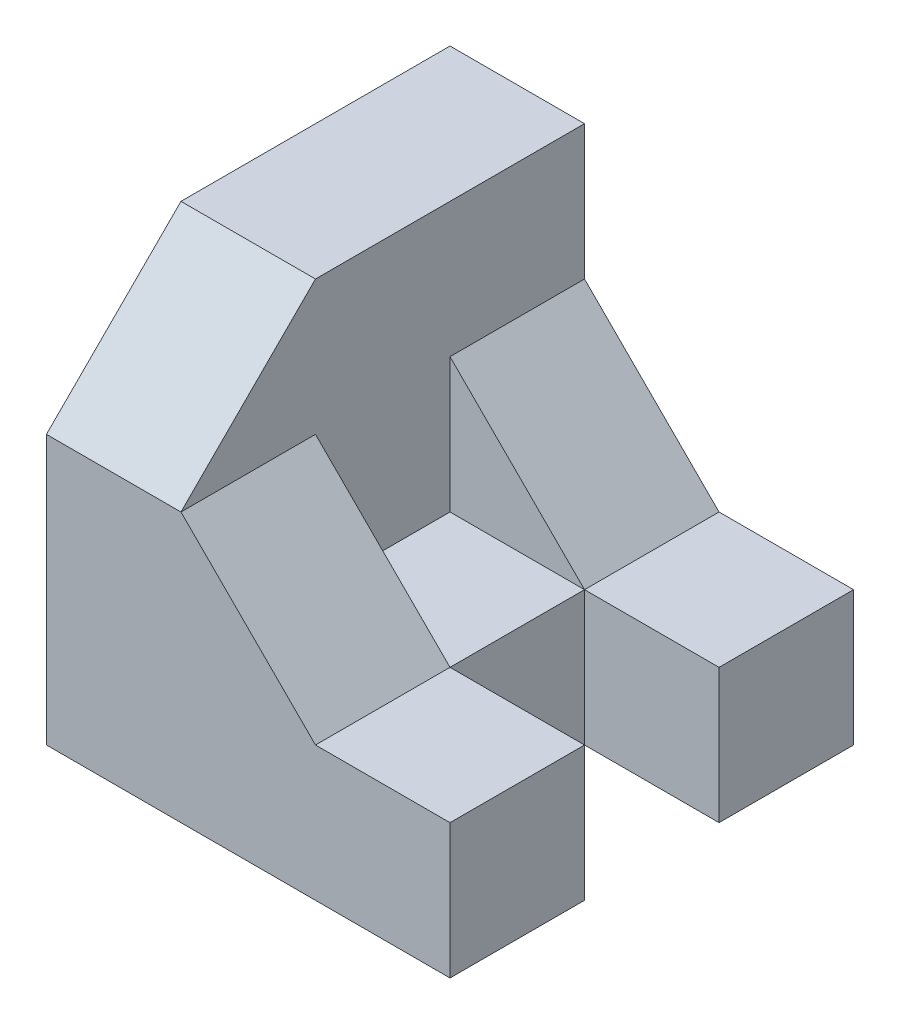
SolidWorks part; units mm, degrees
ref_plane "Alzado" through (0, 0, 0) normal (0, 0, 1) x (1, 0, 0)
ref_plane "Planta" through (0, 0, 0) normal (0, 1, 0) x (1, 0, 0)
ref_plane "Vista lateral" through (0, 0, 0) normal (1, 0, 0) x (0, 0, -1)
sketch "Croquis1" plane through (0, 0, 0) normal (0, 0, 1) x (1, 0, 0)
  line L0 (0, 0) -> (60, 0)
  line L1 (60, 0) -> (60, 60)
  line L2 (60, 60) -> (0, 60)
  line L3 (0, 60) -> (0, 0)
  dimension "D1" = 60
  dimension "D2" = 60
extrude "Saliente-Extruir1" add sketch "Croquis1" against normal blind 60
sketch "Croquis2" plane through (0, 60, 0) normal (0, 1, 0) x (1, 0, 0)
  line L0 (60, 40) -> (20, 40)
  line L1 (60, 60) -> (60, 0) construction
  line L2 (20, 40) -> (20, 20)
  line L3 (20, 20) -> (60, 20)
  line L4 (60, 20) -> (60, 40)
  line L5 (60, 60) -> (0, 60) construction
  line L6 (60, 0) -> (0, 0) construction
  line L7 (0, 60) -> (0, 0) construction
  dimension "D1" = 20
  dimension "D2" = 20
  dimension "D3" = 20
extrude "Cortar-Extruir1" cut sketch "Croquis2" against normal blind 60
sketch "Croquis3" plane through (0, 0, -40) normal (0, 0, 1) x (1, 0, 0)
  line L0 (40, 0) -> (40, 20)
  line L1 (0, 0) -> (60, 0) construction
  line L2 (40, 20) -> (20, 20)
  line L3 (20, 20) -> (20, 0)
  line L4 (20, 0) -> (40, 0)
  line L5 (0, 60) -> (0, 0) construction
  line L6 (60, 0) -> (60, 60) construction
  dimension "D1" = 20
  dimension "D2" = 20
  dimension "D3" = 20
extrude "Saliente-Extruir2" add sketch "Croquis3" along normal blind 20
sketch "Croquis4" plane through (0, 0, -40) normal (0, 0, 1) x (1, 0, 0)
  line L2 (20, 40) -> (40, 20)
  line L3 (40, 20) -> (40, 60)
  line L4 (60, 60) -> (0, 60) construction
  line L5 (40, 60) -> (20, 60)
  line L7 (0, 0) -> (60, 0) construction
  line L8 (60, 0) -> (60, 60) construction
  line L9 (20, 40) -> (20, 60)
  line L10 (40, 20) -> (20, 20) construction
  line L11 (20, 20) -> (20, 40) construction
  dimension "D1" = 20
  dimension "D2" = 20
  dimension "D3" = 20
  dimension "D4" = 40
extrude "Cortar-Extruir2" cut sketch "Croquis4" against normal blind 20
sketch "Croquis5" plane through (0, 0, -20) normal (0, 0, -1) x (-1, 0, 0)
  line L0 (-40, 20) -> (-40, 60)
  line L1 (-40, 60) -> (-20, 60)
  line L2 (-20, 60) -> (-20, 40)
  line L3 (-20, 20) -> (-20, 60) construction
  line L4 (-20, 40) -> (-40, 20)
extrude "Cortar-Extruir3" cut sketch "Croquis5" against normal blind 20
sketch "Croquis6" plane through (20, 0, 0) normal (1, 0, 0) x (0, 0, -1)
  line L0 (0, 40) -> (20, 60)
  line L1 (20, 60) -> (0, 60)
  line L2 (0, 60) -> (0, 40)
extrude "Cortar-Extruir4" cut sketch "Croquis6" against normal blind 20
sketch "Croquis7" plane through (0, 60, 0) normal (0, 1, 0) x (1, 0, 0)
  line L0 (40, 60) -> (40, 40)
  line L1 (40, 40) -> (60, 40)
  line L2 (60, 40) -> (60, 60)
  line L3 (60, 60) -> (40, 60)
extrude "Cortar-Extruir5" cut sketch "Croquis7" against normal blind 40
sketch "Croquis9" plane through (0, 60, 0) normal (0, 1, 0) x (1, 0, 0)
  line L0 (40, 20) -> (40, 0)
  line L1 (40, 0) -> (60, 0)
  line L2 (60, 0) -> (60, 20)
  line L3 (60, 20) -> (40, 20)
extrude "Cortar-Extruir6" cut sketch "Croquis9" against normal blind 40
